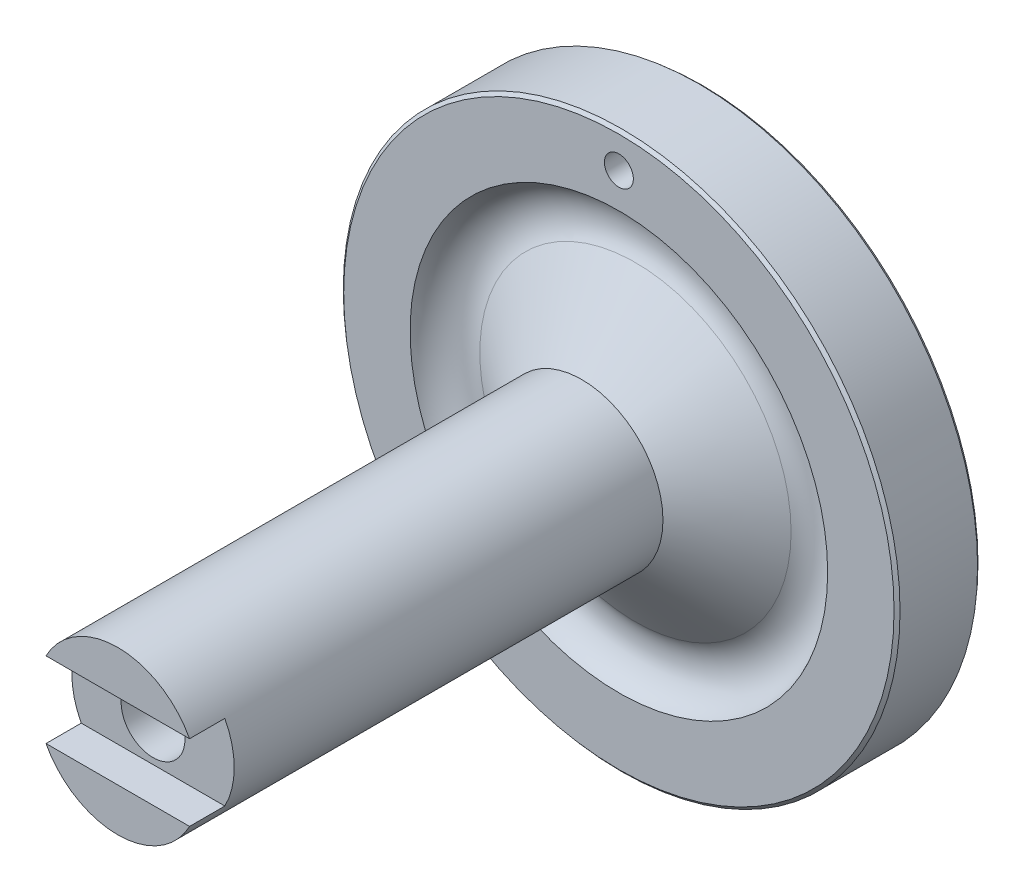
SolidWorks part; units mm, degrees
material "Malleable Cast Iron"
ref_plane "Front Plane" through (0, 0, 0) normal (0, 0, 1) x (1, 0, 0)
ref_plane "Top Plane" through (0, 0, 0) normal (0, 1, 0) x (1, 0, 0)
ref_plane "Right Plane" through (0, 0, 0) normal (1, 0, 0) x (0, 0, -1)
sketch "Sketch1" plane through (0, 0, 0) normal (1, 0, 0) x (0, 0, -1)
  line L0 (0, 0) -> (178.9077, 0) construction
  line L1 (0, 8.7376) -> (0, 22.225)
  line L2 (0, 22.225) -> (127, 22.225)
  line L3 (127, 22.225) -> (141.6976, 42.6022)
  line L4 (137.16, 57.15) -> (137.16, 76.2)
  line L5 (137.16, 76.2) -> (160.02, 76.2)
  line L6 (160.02, 76.2) -> (160.02, 57.15)
  line L7 (160.02, 57.15) -> (144.1458, 35.1416)
  line L8 (152.0952, 15.875) -> (152.0952, 8.7376)
  line L9 (152.0952, 8.7376) -> (0, 8.7376)
  line L10 (0, 22.225) -> (0, 0) construction
  line L11 (145.1358, 22.8344) -> (152.0952, 15.875)
  arc A0 (141.6976, 42.6022) -> (137.16, 57.15) centre (133.9724, 48.1742) ccw
  arc A2 (144.1458, 35.1416) -> (145.1358, 22.8344) centre (151.871, 29.5696) ccw
  dimension "D1" = 152.4
  dimension "D11" = 9.525
  dimension "D13" = 45
  dimension "D14" = 9.525
  dimension "D2" = 44.45
  dimension "D3" = 31.75
  dimension "D4" = 17.4752
  dimension "D5" = 10.16
  dimension "D6" = 22.86
  dimension "D7" = 19.05
  dimension "D8" = 19.05
  dimension "D9" = 127
  dimension "D10" = 6.35
  dimension "D12" = 7.9248
revolve "Revolve1" add sketch "Sketch1" angle 360 about L0
chamfer "Chamfer1" distance 0.762 angle 49 2 edges at (76.2, 0, -160.02) (76.2, 0, -137.16)
sketch "Sketch2" plane through (0, 0, 0) normal (1, 0, 0) x (0, 0, -1)
  line L0 (54.7462, 0) -> (-54.7462, 0) construction
  line L1 (9.652, -10.3886) -> (0, -10.3886)
  line L2 (9.652, -10.3886) -> (9.652, 10.3886)
  line L3 (9.652, 10.3886) -> (0, 10.3886)
  line L4 (0, -10.3886) -> (0, 10.3886)
  line L5 (9.652, -10.3886) -> (0, 10.3886) construction
  line L6 (9.652, 10.3886) -> (0, -10.3886) construction
  line L7 (0, 54.9142) -> (0, -54.9142) construction
  point P0 (4.826, 0)
  dimension "D1" = 9.652
  dimension "D2" = 20.7772
extrude "Cut-Extrude1" cut sketch "Sketch2" against normal through all both and the other way through all
sketch "Sketch3" plane through (0, 0, -160.02) normal (0, 0, -1) x (-1, 0, 0)
  line L0 (0, 76.2) -> (0, 57.15) construction
  circle A0 centre (0, 66.675) radius 3.9624
  circle A1 centre (0, 0) radius 76.2 construction
  circle A2 centre (0, 0) radius 57.15 construction
  dimension "D1" = 7.9248
extrude "Cut-Extrude2" cut sketch "Sketch3" against normal through all
